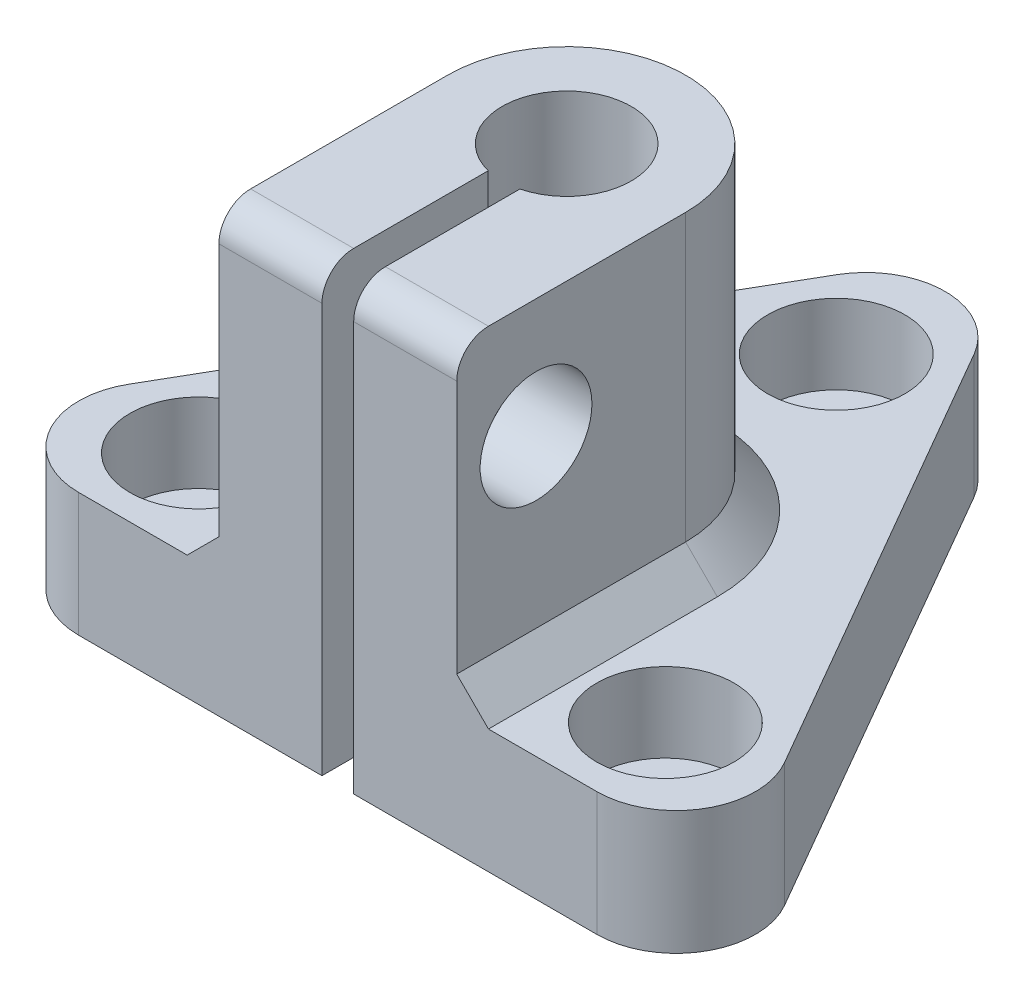
SolidWorks part; units mm, degrees
ref_plane "Plan de face" through (0, 0, 0) normal (0, 0, 1) x (1, 0, 0)
ref_plane "Plan de dessus" through (0, 0, 0) normal (0, 1, 0) x (1, 0, 0)
ref_plane "Plan de droite" through (0, 0, 0) normal (1, 0, 0) x (0, 0, -1)
sketch "Esquisse5" plane through (0, 0, 0) normal (0, 1, 0) x (1, 0, 0)
  line L0 (-25, -14.4338) -> (25, -14.4338)
  line L1 (25, -14.4338) -> (0, 28.8675)
  line L2 (0, 28.8675) -> (-25, -14.4338)
  line L3 (12.5, 7.2169) -> (-25, -14.4338) construction
  line L4 (-12.5, 7.2169) -> (25, -14.4338) construction
  circle A0 centre (0, 17) radius 2.6
  circle A1 centre (-14.7224, -8.5) radius 2.6
  circle A2 centre (14.7224, -8.5) radius 2.6
  dimension "D1" = 5.2
  dimension "D2" = 17
  dimension "D3" = 17
  dimension "D4" = 17
  dimension "D5" = 50
extrude "Boss.-Extru.2" add sketch "Esquisse5" along normal blind 7.8
sketch "Esquisse6" plane through (0, 7.8, 0) normal (0, 1, 0) x (1, 0, 0)
  circle A0 centre (0, 0) radius 7.5
  dimension "D1" = 15
extrude "Boss.-Extru.3" add sketch "Esquisse6" along normal blind 20
sketch "Esquisse13" plane through (0, 27.8, 0) normal (0, 1, 0) x (1, 0, 0)
  line L1 (-7.5, 0) -> (-7.5, -14.4338)
  line L2 (7.5, 0) -> (7.5, -14.4338)
  line L3 (-7.5, -14.4338) -> (7.5, -14.4338)
  line L4 (-25, -14.4338) -> (25, -14.4338) construction
  circle A0 centre (0, 0) radius 7.5 construction
  circle A1 centre (0, 0) radius 7.5 construction
  arc A2 (-7.5, 0) -> (7.5, 0) centre (0, 0) ccw
  point P8 (0, -14.4338)
extrude "Boss.-Extru.6" add sketch "Esquisse13" against normal up to surface (20 mm away) up to face at (0, 7.8, 7.5)
sketch "Esquisse14" plane through (0, 27.8, 0) normal (0, 1, 0) x (1, 0, 0)
  circle A0 centre (0, 0) radius 4.075
  dimension "D1" = 8.15
extrude "Enlèv. mat.-Extru.4" cut sketch "Esquisse14" against normal through all
sketch "Esquisse15" plane through (0, 27.8, 0) normal (0, 1, 0) x (1, 0, 0)
  line L1 (-1, -3.9504) -> (-1, -14.4338)
  line L2 (1, -3.9504) -> (1, -14.4338)
  line L3 (-1, -14.4338) -> (1, -14.4338)
  line L4 (-7.5, -14.4338) -> (7.5, -14.4338) construction
  line L5 (7.5, -14.4338) -> (7.5, 0) construction
  circle A0 centre (0, 0) radius 4.075 construction
  arc A1 (-1, -3.9504) -> (1, -3.9504) centre (0, 0) ccw
  dimension "D1" = 2
extrude "Enlèv. mat.-Extru.5" cut sketch "Esquisse15" against normal through all
fillet "Congé2" radius 5 3 edges at (0, 3.9, -28.8675) (25, 3.9, 14.4338) (-25, 3.9, 14.4338)
sketch "Esquisse17" plane through (7.5, 0, 0) normal (1, 0, 0) x (0, 0, -1)
  line L0 (-14.4338, 27.8) -> (0, 27.8) construction
  line L1 (-14.4338, 7.8) -> (-14.4338, 27.8) construction
  circle A0 centre (-9.4338, 20.3) radius 2.075
  dimension "D1" = 4.15
  dimension "D2" = 7.5
  dimension "D3" = 5
extrude "Enlèv. mat.-Extru.6" cut sketch "Esquisse17" against normal through all
sketch "Esquisse18" plane through (-7.5, 0, 0) normal (-1, 0, 0) x (0, 0, 1)
  line L0 (0, 27.8) -> (14.4338, 27.8) construction
  line L1 (11.4689, 23.825) -> (7.3986, 23.825)
  line L2 (7.3986, 23.825) -> (5.3634, 20.3)
  line L3 (5.3634, 20.3) -> (7.3986, 16.775)
  line L4 (7.3986, 16.775) -> (11.4689, 16.775)
  line L5 (11.4689, 16.775) -> (13.5041, 20.3)
  line L6 (13.5041, 20.3) -> (11.4689, 23.825)
  circle A0 centre (9.4338, 20.3) radius 3.525 construction
  dimension "D1" = 7.05
extrude "Enlèv. mat.-Extru.7" cut sketch "Esquisse18" against normal blind 3.25
sketch "Esquisse19" plane through (0, 7.8, 0) normal (0, 1, 0) x (1, 0, 0)
  circle A0 centre (0, 17) radius 4.325
  circle A1 centre (14.7224, -8.5) radius 4.325
  circle A2 centre (-14.7224, -8.5) radius 4.325
  dimension "D1" = 8.65
extrude "Enlèv. mat.-Extru.8" cut sketch "Esquisse19" against normal blind 5
sketch "Esquisse20" plane through (7.5, 0, 0) normal (1, 0, 0) x (0, 0, -1)
  circle A0 centre (-9.4338, 20.3) radius 3.525
  dimension "D1" = 7.05
extrude "Enlèv. mat.-Extru.9" cut sketch "Esquisse20" against normal blind 4.97
fillet "Congé3" radius 2 1 edges at (-4.25, 27.8, 14.4338)
chamfer "Chanfrein2" distance 2 angle 45 3 edges at (-7.5, 7.8, 7.2169) (0, 7.8, -7.5) (7.5, 7.8, 7.2169)
sketch "Esquisse21" plane through (2.53, 0, 0) normal (1, 0, 0) x (0, 0, -1)
  line L0 (-10.3929, 22.14) -> (-8.4746, 22.14)
  line L1 (-8.4746, 22.14) -> (-9.4338, 22.64)
  line L2 (-9.4338, 22.64) -> (-10.3929, 22.14)
  line L3 (-12.4338, 27.8) -> (0, 27.8) construction
  circle A0 centre (-9.4338, 20.3) radius 2.075 construction
  dimension "D1" = 0.5
extrude "Enlèv. mat.-Extru.10" cut sketch "Esquisse21" against normal through all
